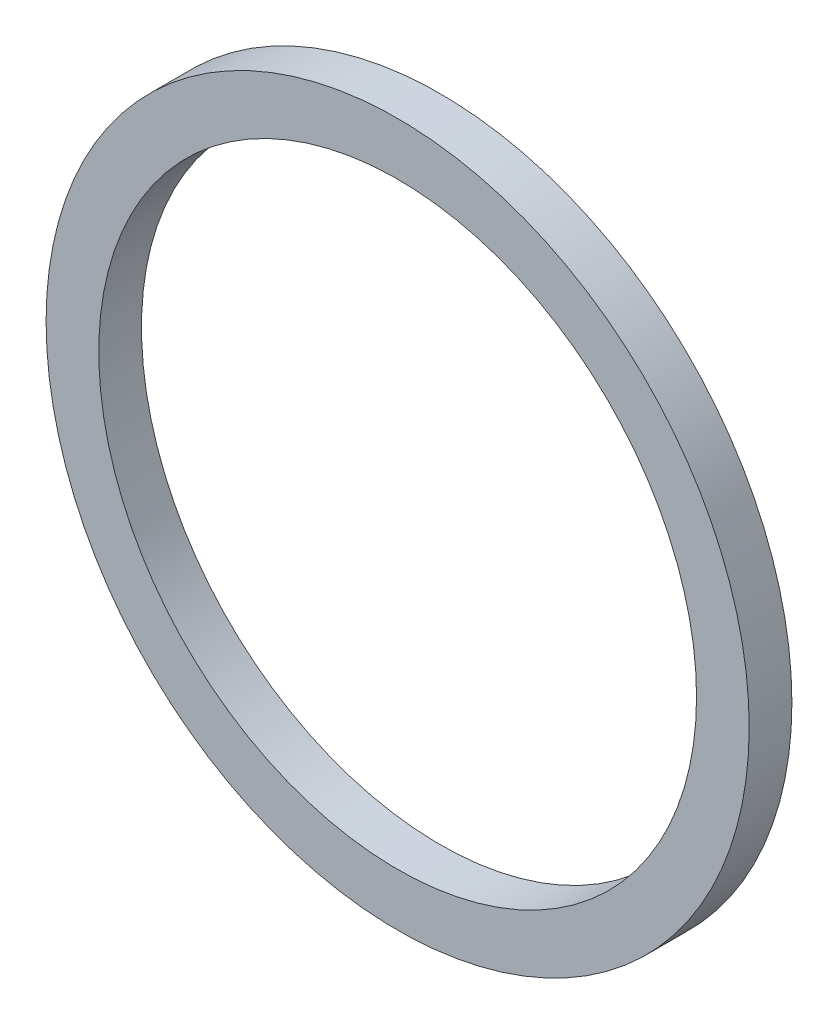
SolidWorks part; units mm, degrees
ref_plane "Front Plane" through (0, 0, 0) normal (0, 0, 1) x (1, 0, 0)
ref_plane "Top Plane" through (0, 0, 0) normal (0, 1, 0) x (1, 0, 0)
ref_plane "Right Plane" through (0, 0, 0) normal (1, 0, 0) x (0, 0, -1)
sketch "Sketch1" plane through (0, 0, 0) normal (0, 0, 1) x (1, 0, 0)
  circle A0 centre (0, 0) radius 24.7
  circle A1 centre (0, 0) radius 21
  dimension "D1" = 49.4
  dimension "D2" = 42
extrude "Boss-Extrude1" add sketch "Sketch1" along normal blind 3
